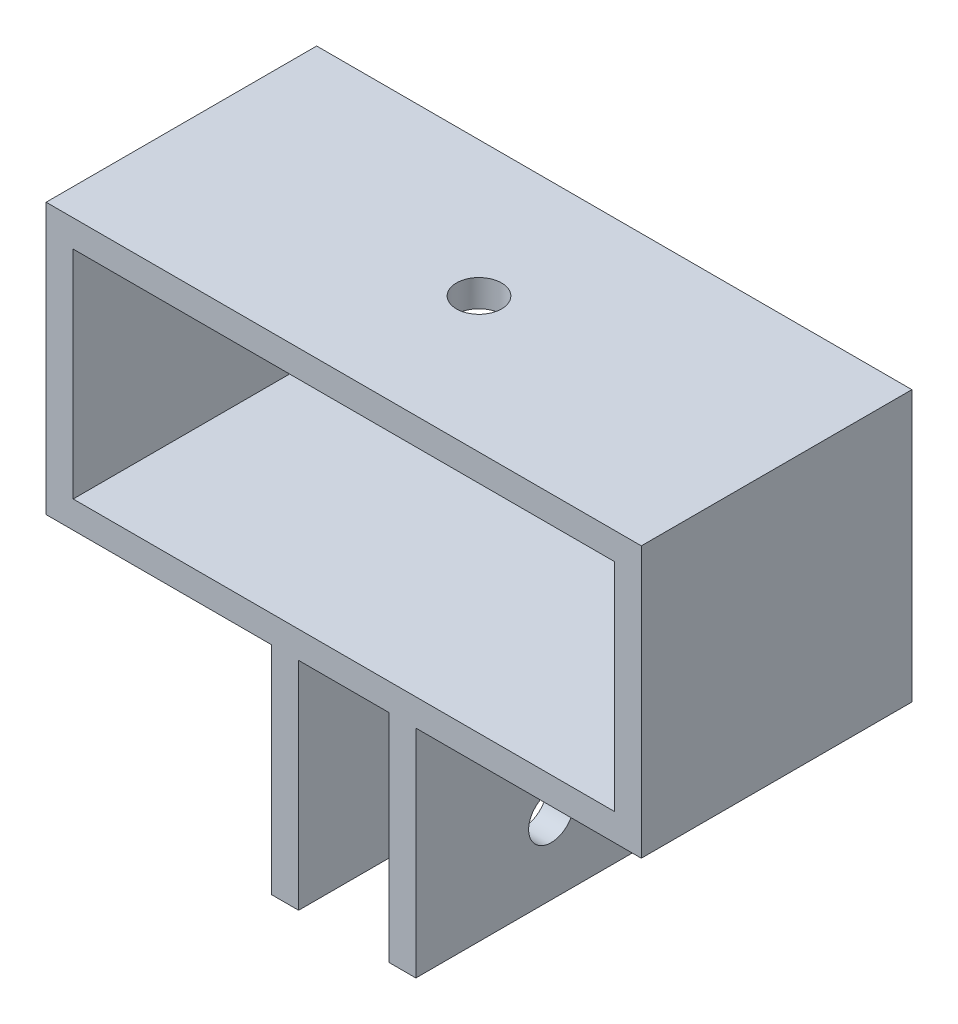
SolidWorks part; units mm, degrees
ref_plane "Front Plane" through (0, 0, 0) normal (0, 0, 1) x (1, 0, 0)
ref_plane "Top Plane" through (0, 0, 0) normal (0, 1, 0) x (1, 0, 0)
ref_plane "Right Plane" through (0, 0, 0) normal (1, 0, 0) x (0, 0, -1)
sketch "Sketch1" plane through (0, 0, 0) normal (0, 1, 0) x (1, 0, 0)
  line L1 (-33, 15) -> (33, 15)
  line L2 (-33, 15) -> (-33, -15)
  line L3 (-33, -15) -> (33, -15)
  line L4 (33, 15) -> (33, -15)
  line L5 (-33, 15) -> (33, -15) construction
  line L6 (-33, -15) -> (33, 15) construction
  point P0 (0, 0)
  dimension "D1" = 66
  dimension "D2" = 30
extrude "Boss-Extrude1" add sketch "Sketch1" along normal blind 30
sketch "Sketch2" plane through (0, 0, 15) normal (0, 0, 1) x (1, 0, 0)
  line L0 (0, 0) -> (0, 30)
  line L1 (-33, 30) -> (33, 30) construction
  line L3 (-30, 27) -> (30, 27)
  line L4 (-30, 27) -> (-30, 3)
  line L5 (-30, 3) -> (30, 3)
  line L6 (30, 27) -> (30, 3)
  line L7 (-30, 27) -> (30, 3) construction
  line L8 (-30, 3) -> (30, 27) construction
  point P5 (0, 15)
  dimension "D1" = 24
  dimension "D2" = 60
extrude "Cut-Extrude1" cut sketch "Sketch2" against normal through all contours L6 L3 L0 L5 | L4 L5 L0 L3
sketch "Sketch3" plane through (0, 30, 0) normal (0, 1, 0) x (1, 0, 0)
  circle A0 centre (0, 0) radius 2.5
  dimension "D1" = 5
extrude "Cut-Extrude2" cut sketch "Sketch3" against normal blind 10
sketch "Sketch4" plane through (0, 0, 0) normal (0, -1, 0) x (1, 0, 0)
  line L0 (33, -15) -> (-33, -15) construction
  line L1 (-8, 15) -> (8, 15)
  line L2 (-8, 15) -> (-8, -15)
  line L3 (-8, -15) -> (8, -15)
  line L4 (8, 15) -> (8, -15)
  line L5 (-8, 15) -> (8, -15) construction
  line L6 (-8, -15) -> (8, 15) construction
  point P0 (0, 0)
  dimension "D1" = 16
extrude "Boss-Extrude2" add sketch "Sketch4" along normal blind 24
sketch "Sketch5" plane through (0, 0, 15) normal (0, 0, 1) x (1, 0, 0)
  line L0 (8, -24) -> (-8, -24) construction
  line L1 (0, -24) -> (0, 0)
  line L3 (-5, 0) -> (5, 0)
  line L4 (-5, 0) -> (-5, -24)
  line L5 (-5, -24) -> (5, -24)
  line L6 (5, 0) -> (5, -24)
  line L7 (-5, 0) -> (5, -24) construction
  line L8 (-5, -24) -> (5, 0) construction
  point P2 (0, -12)
  dimension "D1" = 10
extrude "Cut-Extrude3" cut sketch "Sketch5" against normal through all contours L6 L5 L4 L3
sketch "Sketch6" plane through (8, 0, 0) normal (1, 0, 0) x (0, 0, -1)
  line L0 (0, -24) -> (0, -16)
  line L1 (15, -24) -> (-15, -24) construction
  circle A0 centre (0, -16) radius 2.5
  dimension "D2" = 5
  dimension "D1" = 8
extrude "Cut-Extrude4" cut sketch "Sketch6" against normal blind 24
